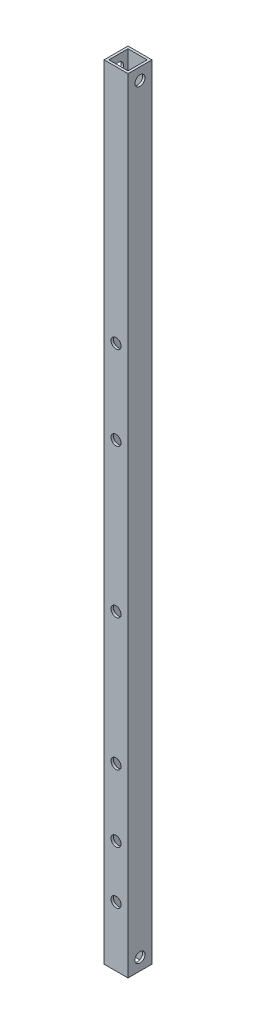
SolidWorks part; units mm, degrees
material "5052-H34"
ref_plane "正面" through (0, 0, 0) normal (0, 0, 1) x (1, 0, 0)
ref_plane "平面" through (0, 0, 0) normal (0, 1, 0) x (1, 0, 0)
ref_plane "右側面" through (0, 0, 0) normal (1, 0, 0) x (0, 0, -1)
sketch "ｽｹｯﾁ1" plane through (0, 0, 0) normal (0, 1, 0) x (1, 0, 0)
  line L1 (-5, 5) -> (5, 5)
  line L2 (-5, 5) -> (-5, -5)
  line L3 (-5, -5) -> (5, -5)
  line L4 (5, 5) -> (5, -5)
  line L5 (-5, 5) -> (5, -5) construction
  line L6 (-5, -5) -> (5, 5) construction
  point P0 (0, 0)
  dimension "D1" = 10
extrude "押し出し-薄板1" add sketch "ｽｹｯﾁ1" along normal blind 327 thin
sketch "ｽｹｯﾁ2" plane through (5, 0, 0) normal (1, 0, 0) x (0, 0, -1)
  line L0 (0, 0) -> (0, 322) construction
  line L1 (-5, 0) -> (5, 0) construction
  circle A0 centre (0, 322) radius 2.1
  circle A1 centre (0, 5) radius 2.1
  dimension "D3" = 4.2
  dimension "D1" = 317
  dimension "D2" = 5
extrude "ｶｯﾄ - 押し出し1" cut sketch "ｽｹｯﾁ2" against normal through all
sketch "ｽｹｯﾁ3" plane through (0, 0, -5) normal (0, 0, -1) x (-1, 0, 0)
  line L0 (0, 0) -> (0, 130) construction
  circle A0 centre (0, 130) radius 2.1
  circle A1 centre (0, 75) radius 2.1
  circle A2 centre (0, 47) radius 2.1
  circle A3 centre (0, 25) radius 2.1
  dimension "D2" = 4.2
  dimension "D1" = 55
  dimension "D3" = 75
  dimension "D4" = 22
  dimension "D5" = 25
extrude "ｶｯﾄ - 押し出し2" cut sketch "ｽｹｯﾁ3" against normal through all
sketch "ｽｹｯﾁ4" plane through (0, 0, 5) normal (0, 0, 1) x (1, 0, 0)
  line L0 (0, 327) -> (0, 192) construction
  line L1 (-5, 327) -> (5, 327) construction
  circle A0 centre (0, 192) radius 2.1
  circle A1 centre (0, 227) radius 2.1
  dimension "D1" = 4.2
  dimension "D2" = 35
  dimension "D3" = 100
extrude "ｶｯﾄ - 押し出し3" cut sketch "ｽｹｯﾁ4" against normal through all
